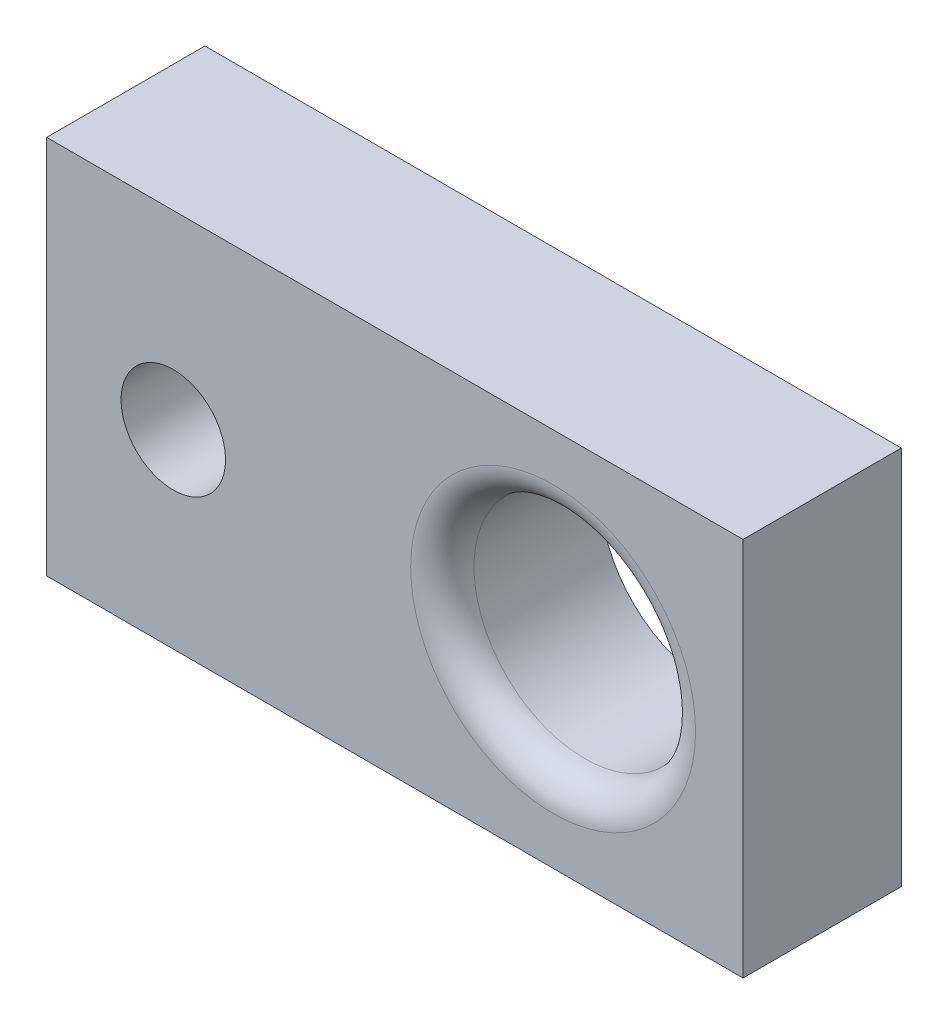
SolidWorks part; units mm, degrees
material "Latão"
ref_plane "Plano frontal" through (0, 0, 0) normal (0, 0, 1) x (1, 0, 0)
ref_plane "Plano superior" through (0, 0, 0) normal (0, 1, 0) x (1, 0, 0)
ref_plane "Plano direito" through (0, 0, 0) normal (1, 0, 0) x (0, 0, -1)
sketch "Esboço1" plane through (0, 0, 0) normal (0, 0, 1) x (1, 0, 0)
  line L1 (-54.6494, -3.5591) -> (-32.6494, -3.5591)
  line L2 (-54.6494, -3.5591) -> (-54.6494, -15.5591)
  line L3 (-54.6494, -15.5591) -> (-32.6494, -15.5591)
  line L4 (-32.6494, -3.5591) -> (-32.6494, -15.5591)
  dimension "D1" = 12
  dimension "D2" = 22
extrude "Ressalto-extrusão1" add sketch "Esboço1" along normal blind 5
hole_wizard "Broca de rosquear para tarraxa de M8x1.01" positions "Esboço3" profile "Esboço2" hole size "M8x1.0" standard "Métrico Ansi" end condition up to next
sketch "Esboço3" plane through (0, 0, 5) normal (0, 0, 1) x (1, 0, 0)
  line L0 (-32.6494, -3.5591) -> (-54.6494, -3.5591) construction
  line L2 (-32.6494, -15.5591) -> (-32.6494, -3.5591) construction
  point P0 (-38.6494, -9.5591)
  dimension "D1" = 6
  dimension "D2" = 6
cosmetic thread "Representação de rosca1" parameters "D2"=10
sketch "Esboço2" plane through (-38.6494, -9.5591, 5) normal (1, 0, 0) x (0, -1, 0)
  line L0 (0, 0) -> (0, 5)
  line L1 (0, 5) -> (3.5, 5)
  line L2 (3.5, 5) -> (3.5, 0)
  line L5 (3.5, 0) -> (0, 0)
  line L11 (0, -6.35) -> (0, 107.95) construction
  dimension "Thru Hole Dia." = 7
  dimension "Thru Hole Depth" = 5
hole_wizard "Broca de rosquear para tarraxa de M4x0.71" positions "Esboço5" profile "Esboço4" hole size "M4x0.7" standard "Métrico Ansi" end condition up to next
sketch "Esboço5" plane through (0, 0, 5) normal (0, 0, 1) x (1, 0, 0)
  line L0 (-32.6494, -3.5591) -> (-54.6494, -3.5591) construction
  circle A1 centre (-38.6494, -9.5591) radius 3.5 construction
  point P1 (-50.6494, -9.5591)
  dimension "D1" = 12
  dimension "D2" = 6
sketch "Esboço4" plane through (-50.6494, -9.5591, 5) normal (1, 0, 0) x (0, -1, 0)
  line L0 (0, 0) -> (0, 5)
  line L1 (0, 5) -> (1.65, 5)
  line L2 (1.65, 5) -> (1.65, 0)
  line L5 (1.65, 0) -> (0, 0)
  line L11 (0, -6.35) -> (0, 107.95) construction
  dimension "Thru Hole Dia." = 3.3
  dimension "Thru Hole Depth" = 5
cosmetic thread "Representação de rosca2" parameters "D1"=5, "D2"=4
fillet "Filete1" radius 1 1 edges at (-35.1494, -9.5591, 5)
